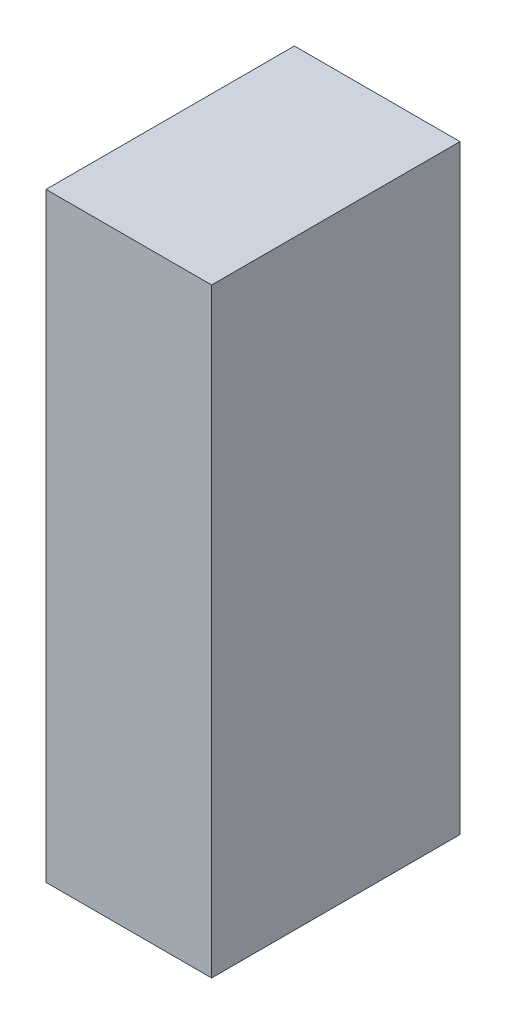
SolidWorks part; units mm, degrees
ref_plane "Plan de face" through (0, 0, 0) normal (0, 0, 1) x (1, 0, 0)
ref_plane "Plan de dessus" through (0, 0, 0) normal (0, 1, 0) x (1, 0, 0)
ref_plane "Plan de droite" through (0, 0, 0) normal (1, 0, 0) x (0, 0, -1)
sketch "Esquisse1" plane through (0, 0, 0) normal (0, 1, 0) x (1, 0, 0)
  line L1 (4, -6) -> (-4, -6)
  line L2 (4, -6) -> (4, 6)
  line L3 (4, 6) -> (-4, 6)
  line L4 (-4, -6) -> (-4, 6)
  line L5 (4, -6) -> (-4, 6) construction
  line L6 (4, 6) -> (-4, -6) construction
  point P0 (0, 0)
  dimension "D1" = 8
  dimension "D2" = 12
extrude "Boss.-Extru.1" add sketch "Esquisse1" along normal blind 29
